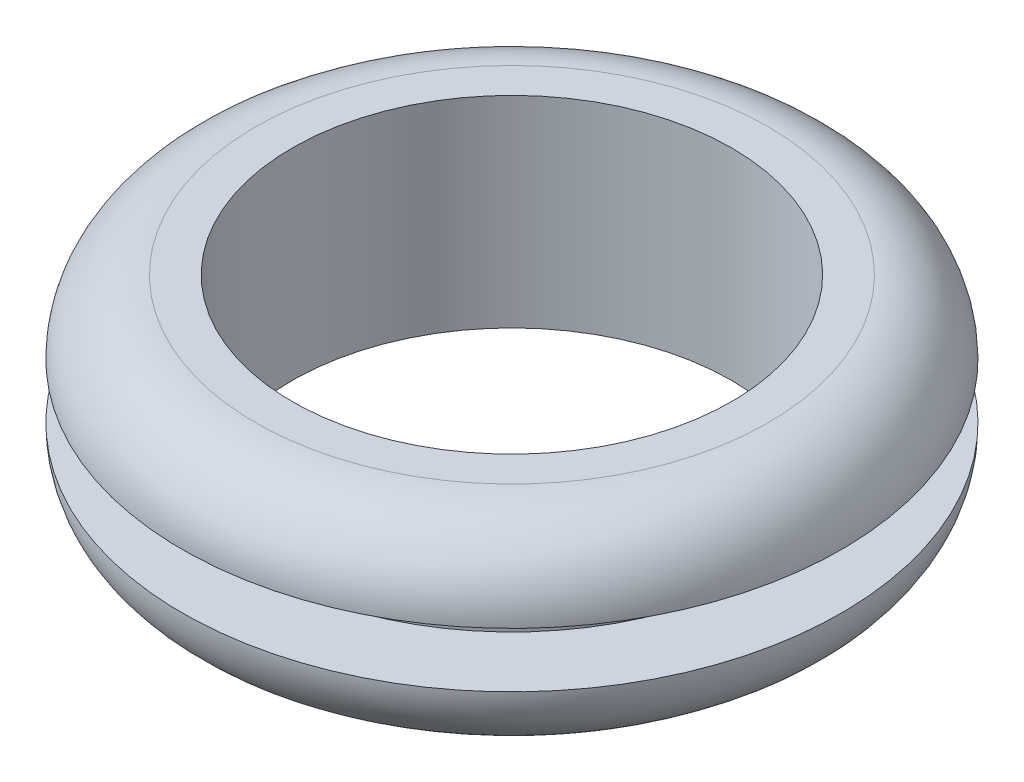
SolidWorks part; units mm, degrees
material "Rubber"
ref_plane "Front" through (0, 0, 0) normal (0, 0, 1) x (1, 0, 0)
ref_plane "Top" through (0, 0, 0) normal (0, 1, 0) x (1, 0, 0)
ref_plane "Right" through (0, 0, 0) normal (1, 0, 0) x (0, 0, -1)
sketch "Sketch1" plane through (0, 0, 0) normal (1, 0, 0) x (0, 0, -1)
  line L0 (0, -4.3656) -> (0, 4.3656) construction
  line L1 (0, 1.1906) -> (0, -1.1906) construction
  line L2 (-14.2875, 4.3656) -> (14.2875, 4.3656) construction
  line L3 (-9.525, 1.1906) -> (9.525, 1.1906) construction
  line L4 (-11.1125, 0) -> (11.1125, 0) construction
  point P12 (-9.525, 1.1906)
  point P13 (9.525, 1.1906)
  point P14 (-11.1125, 0)
  point P15 (11.1125, 0)
  point P16 (-14.2875, 4.3656)
  point P17 (0, -4.3656)
  point P18 (14.2875, 4.3656)
  point P19 (0, 4.3656)
  point P20 (0, 1.1906)
  point P21 (0, -1.1906)
  dimension "Overall Height E" = 8.7312
  dimension "Material Thickness B" = 2.3813
  dimension "Flange Diameter D" = 28.575
  dimension "ID C" = 19.05
  dimension "For ID A" = 22.225
sketch "Sketch2" plane through (0, 0, 0) normal (1, 0, 0) x (0, 0, -1)
  line L0 (-9.525, -4.3656) -> (-9.525, 4.3656)
  line L1 (-9.525, 4.3656) -> (-11.1125, 4.3656)
  line L2 (-11.1125, 1.1906) -> (-11.1125, -1.1906)
  line L3 (-11.1125, 1.1906) -> (-14.2875, 1.1906)
  line L4 (-11.1125, -1.1906) -> (-14.2875, -1.1906)
  line L5 (-9.525, -4.3656) -> (-11.1125, -4.3656)
  arc A0 (-14.2875, 1.1906) -> (-11.1125, 4.3656) centre (-11.1125, 1.1906) cw
  arc A1 (-14.2875, -1.1906) -> (-11.1125, -4.3656) centre (-11.1125, -1.1906) ccw
  point P4 (-14.2875, 1.1906)
revolve "Revolve1" add sketch "Sketch2" angle 360 about L0
ref_plane "Plane1" through (0, 4.3656, 0) normal (0, -1, 0) x (0, 0, -1)
sketch "Sketch3" plane through (0, 4.3656, 0) normal (0, -1, 0) x (0, 0, -1)
  line L0 (0, -14.2875) -> (0, 14.2875) construction
  line L1 (-14.2875, 0) -> (14.2875, 0) construction
  line L2 (0, 9.525) -> (0, -9.525) construction
  line L3 (-9.525, 0) -> (9.525, 0) construction
  line L4 (0, 11.1125) -> (0, -11.1125) construction
  line L5 (-11.1125, 0) -> (11.1125, 0) construction
  point P11 (0, 14.2875)
  point P12 (0, 9.525)
  point P13 (0, -9.525)
  point P14 (0, -14.2875)
  point P19 (0, -11.1125)
  point P20 (0, 11.1125)
